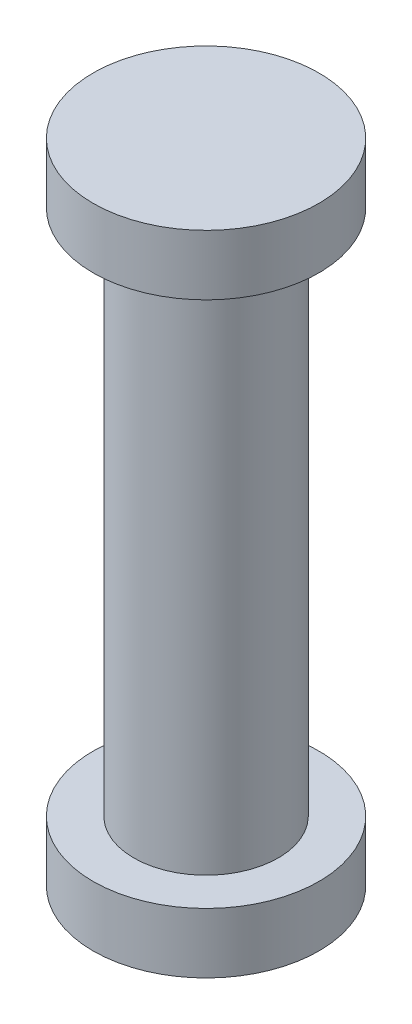
SolidWorks part; units mm, degrees
ref_plane "Front Plane" through (0, 0, 0) normal (0, 0, 1) x (1, 0, 0)
ref_plane "Top Plane" through (0, 0, 0) normal (0, 1, 0) x (1, 0, 0)
ref_plane "Right Plane" through (0, 0, 0) normal (1, 0, 0) x (0, 0, -1)
sketch "Sketch1" plane through (0, 0, 0) normal (0, 1, 0) x (1, 0, 0)
  circle A0 centre (0, 0) radius 3.048
  dimension "D1" = 6.096
extrude "Boss-Extrude1" add sketch "Sketch1" along normal mid plane 22.225
sketch "Sketch2" plane through (0, 11.1125, 0) normal (0, 1, 0) x (1, 0, 0)
  circle A0 centre (0, 0) radius 4.7625
  dimension "D1" = 9.525
extrude "Boss-Extrude2" add sketch "Sketch2" along normal blind 2.54
mirror "Mirror1" about plane through (0, 0, 0) normal (0, 1, 0) of "Boss-Extrude2"
